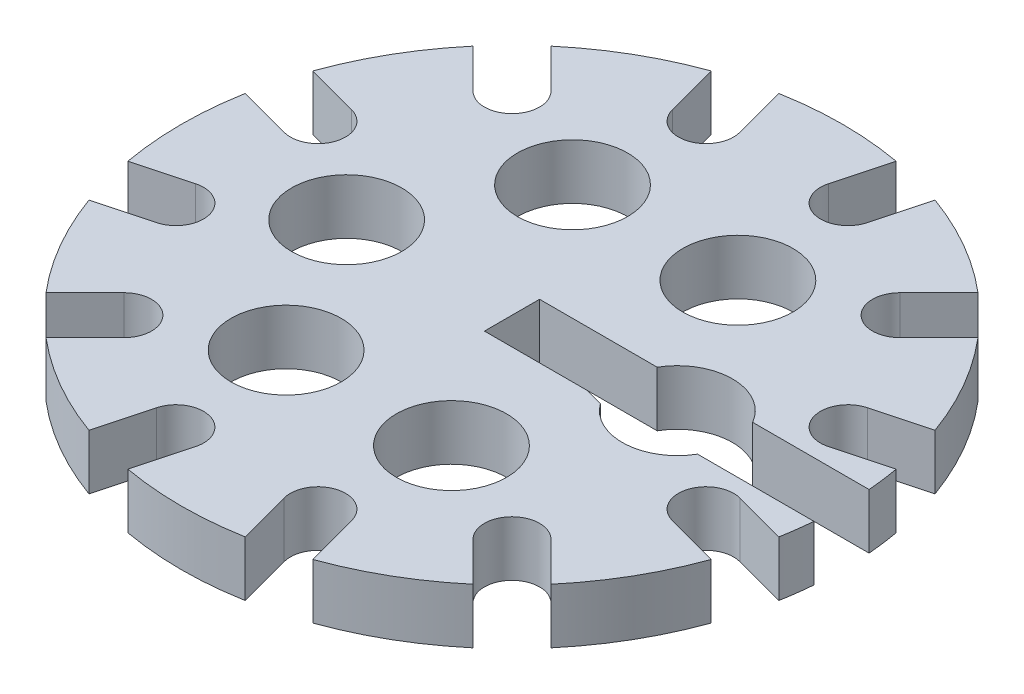
SolidWorks part; units mm, degrees
ref_plane "Front Plane" through (0, 0, 0) normal (0, 0, 1) x (1, 0, 0)
ref_plane "Top Plane" through (0, 0, 0) normal (0, 1, 0) x (1, 0, 0)
ref_plane "Right Plane" through (0, 0, 0) normal (1, 0, 0) x (0, 0, -1)
sketch "Sketch1" plane through (0, 0, 0) normal (0, 1, 0) x (1, 0, 0)
  line L0 (0, 0) -> (0, -5.455)
  line L5 (0, -5.455) -> (23.2817, -5.455)
  line L6 (0, 0) -> (0, 5.455)
  line L7 (0, 5.455) -> (23.2817, 5.455)
  line L8 (52.4616, -14.0571) -> (0, 0)
  line L9 (42.2618, -34.5473) -> (49.9764, -42.2618)
  line L10 (53.8735, -8.7879) -> (64.4117, -11.6116)
  line L11 (51.0498, -19.3262) -> (61.588, -22.1499)
  line L12 (34.5473, -42.2618) -> (42.2618, -49.9764)
  line L13 (19.3262, -51.0498) -> (22.1499, -61.588)
  line L14 (8.7879, -53.8735) -> (11.6116, -64.4117)
  line L15 (-8.7879, -53.8735) -> (-11.6116, -64.4117)
  line L16 (-19.3262, -51.0498) -> (-22.1499, -61.588)
  line L17 (-34.5473, -42.2618) -> (-42.2618, -49.9764)
  line L18 (-42.2618, -34.5473) -> (-49.9764, -42.2618)
  line L19 (-51.0498, -19.3262) -> (-61.588, -22.1499)
  line L20 (-53.8735, -8.7879) -> (-64.4117, -11.6116)
  line L21 (-53.8735, 8.7879) -> (-64.4117, 11.6116)
  line L22 (-51.0498, 19.3262) -> (-61.588, 22.1499)
  line L23 (-42.2618, 34.5473) -> (-49.9764, 42.2618)
  line L24 (-34.5473, 42.2618) -> (-42.2618, 49.9764)
  line L25 (-19.3262, 51.0498) -> (-22.1499, 61.588)
  line L26 (-8.7879, 53.8735) -> (-11.6116, 64.4117)
  line L27 (8.7879, 53.8735) -> (11.6116, 64.4117)
  line L28 (19.3262, 51.0498) -> (22.1499, 61.588)
  line L29 (34.5473, 42.2618) -> (42.2618, 49.9764)
  line L30 (42.2618, 34.5473) -> (49.9764, 42.2618)
  line L31 (51.0498, 19.3262) -> (61.588, 22.1499)
  line L32 (53.8735, 8.7879) -> (64.4117, 11.6116)
  line L33 (42.1783, 5.455) -> (65.2223, 5.455)
  line L34 (42.1783, -5.455) -> (65.2223, -5.455)
  arc A0 (65.2223, 5.455) -> (64.4117, 11.6116) centre (0, 0) ccw
  arc A1 (53.8735, -8.7879) -> (51.0498, -19.3262) centre (52.4616, -14.0571) ccw
  arc A2 (64.4117, -11.6116) -> (65.2223, -5.455) centre (0, 0) ccw
  arc A3 (42.2618, -34.5473) -> (34.5473, -42.2618) centre (38.4046, -38.4046) ccw
  arc A4 (19.3262, -51.0498) -> (8.7879, -53.8735) centre (14.0571, -52.4616) ccw
  arc A5 (-8.7879, -53.8735) -> (-19.3262, -51.0498) centre (-14.0571, -52.4616) ccw
  arc A6 (-34.5473, -42.2618) -> (-42.2618, -34.5473) centre (-38.4046, -38.4046) ccw
  arc A7 (-51.0498, -19.3262) -> (-53.8735, -8.7879) centre (-52.4616, -14.0571) ccw
  arc A8 (-53.8735, 8.7879) -> (-51.0498, 19.3262) centre (-52.4616, 14.0571) ccw
  arc A9 (-42.2618, 34.5473) -> (-34.5473, 42.2618) centre (-38.4046, 38.4046) ccw
  arc A10 (-19.3262, 51.0498) -> (-8.7879, 53.8735) centre (-14.0571, 52.4616) ccw
  arc A11 (8.7879, 53.8735) -> (19.3262, 51.0498) centre (14.0571, 52.4616) ccw
  arc A12 (34.5473, 42.2618) -> (42.2618, 34.5473) centre (38.4046, 38.4046) ccw
  arc A13 (51.0498, 19.3262) -> (53.8735, 8.7879) centre (52.4616, 14.0571) ccw
  arc A14 (49.9764, -42.2618) -> (61.588, -22.1499) centre (0, 0) ccw
  arc A15 (22.1499, -61.588) -> (42.2618, -49.9764) centre (0, 0) ccw
  arc A16 (-11.6116, -64.4117) -> (11.6116, -64.4117) centre (0, 0) ccw
  arc A17 (-42.2618, -49.9764) -> (-22.1499, -61.588) centre (0, 0) ccw
  arc A18 (-61.588, -22.1499) -> (-49.9764, -42.2618) centre (0, 0) ccw
  arc A19 (-64.4117, 11.6116) -> (-64.4117, -11.6116) centre (0, 0) ccw
  arc A20 (-49.9764, 42.2618) -> (-61.588, 22.1499) centre (0, 0) ccw
  arc A21 (-22.1499, 61.588) -> (-42.2618, 49.9764) centre (0, 0) ccw
  arc A22 (11.6116, 64.4117) -> (-11.6116, 64.4117) centre (0, 0) ccw
  arc A23 (42.2618, 49.9764) -> (22.1499, 61.588) centre (0, 0) ccw
  arc A24 (61.588, 22.1499) -> (49.9764, 42.2618) centre (0, 0) ccw
  circle A26 centre (-32.73, 0) radius 10.91
  circle A27 centre (-16.365, 28.345) radius 10.91
  circle A28 centre (16.365, 28.345) radius 10.91
  arc A29 (23.2817, -5.455) -> (42.1783, -5.455) centre (32.73, 0) ccw
  circle A30 centre (16.365, -28.345) radius 10.91
  circle A31 centre (-16.365, -28.345) radius 10.91
  arc A32 (42.1783, 5.455) -> (23.2817, 5.455) centre (32.73, 0) ccw
  dimension "D1" = 130.9
  dimension "D7" = 10.91
  dimension "D5" = 10.91
  dimension "D10" = 21.82
  dimension "D2" = 10.91
  dimension "D3" = 5.455
  dimension "D4" = 15
  dimension "D6" = 5.455
  dimension "D8" = 10.91
  dimension "D11" = 32.73
  dimension "D9" = 12
  dimension "D12" = 6
extrude "Boss-Extrude1" add sketch "Sketch1" along normal blind 10.91 contours A29 L8 A1 L10 A2 L34 | A32 L33 A0 L32 A13 L31 A24 L30 A12 L29 A23 L28 A11 L27 A22 L26 A10 L25 A21 L24 A9 L23 A20 L22 A8 L21 A19 L20 A7 L19 A18 L18 A6 L17 A17 L16 A5 L15 A16 L14 A4 L13 A15 L12 A3 L9 A14 L11 A1 L8 A29
